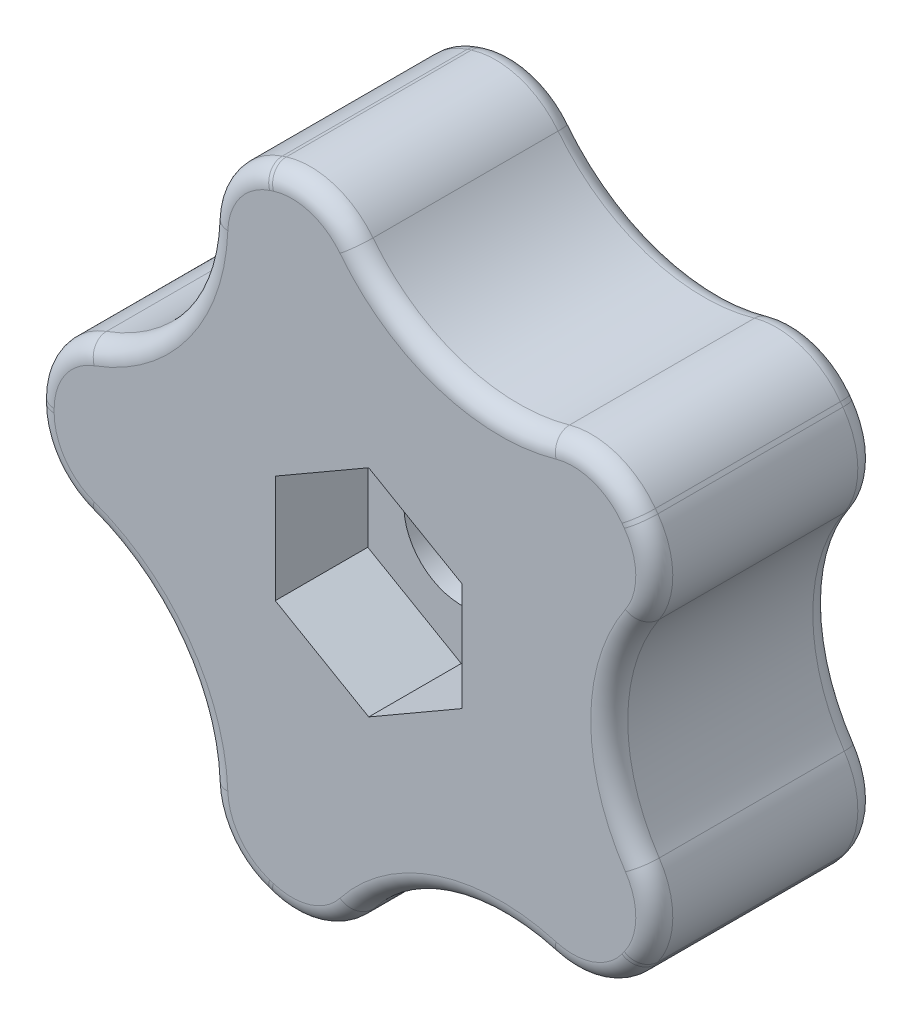
SolidWorks part; units mm, degrees
ref_plane "Plan de face" through (0, 0, 0) normal (0, 0, 1) x (1, 0, 0)
ref_plane "Plan de dessus" through (0, 0, 0) normal (0, 1, 0) x (1, 0, 0)
ref_plane "Plan de droite" through (0, 0, 0) normal (1, 0, 0) x (0, 0, -1)
sketch "Esquisse1" plane through (0, 0, 0) normal (0, 0, 1) x (1, 0, 0)
  circle A0 centre (0, 0) radius 18
  dimension "D1" = 36
extrude "Boss.-Extru.1" add sketch "Esquisse1" along normal blind 12
sketch "Esquisse2" plane through (0, 0, 0) normal (0, 0, -1) x (-1, 0, 0)
  circle A0 centre (0, 0) radius 6
  dimension "D1" = 12
extrude "Boss.-Extru.2" add sketch "Esquisse2" along normal blind 3
sketch "Esquisse3" plane through (0, 0, 12) normal (0, 0, 1) x (1, 0, 0)
  circle A0 centre (0, 0) radius 3.1
  dimension "D1" = 6.2
extrude "Enlèv. mat.-Extru.1" cut sketch "Esquisse3" against normal through all both and the other way through all
sketch "Esquisse4" plane through (0, 0, 12) normal (0, 0, 1) x (1, 0, 0)
  circle A0 centre (0, 0) radius 5
  dimension "D1" = 10
extrude "Enlèv. mat.-Extru.2" [suppressed] cut sketch "Esquisse4" against normal blind 8
sketch "Esquisse5" plane through (0, 0, 12) normal (0, 0, 1) x (1, 0, 0)
  line L0 (0, 0) -> (23, 0) construction
  arc A0 (16.3696, -7.4858) -> (16.3696, 7.4858) centre (23, 0) cw
  circle A1 centre (0, 0) radius 18 construction
  arc A2 (16.3696, -7.4858) -> (16.3696, 7.4858) centre (0, 0) ccw
  arc A3 (-2.061, -17.8816) -> (12.1779, -13.2551) centre (7.1074, -21.8743) cw
  arc A4 (-2.061, -17.8816) -> (12.1779, -13.2551) centre (0, 0) ccw
  arc A5 (-17.6433, -3.5656) -> (-8.8432, -15.6779) centre (-18.6074, -13.5191) cw
  arc A6 (-17.6433, -3.5656) -> (-8.8432, -15.6779) centre (0, 0) ccw
  arc A7 (-8.8432, 15.6779) -> (-17.6433, 3.5656) centre (-18.6074, 13.5191) cw
  arc A8 (-8.8432, 15.6779) -> (-17.6433, 3.5656) centre (0, 0) ccw
  arc A9 (12.1779, 13.2551) -> (-2.061, 17.8816) centre (7.1074, 21.8743) cw
  arc A10 (12.1779, 13.2551) -> (-2.061, 17.8816) centre (0, 0) ccw
  point P23 (0, 0)
  dimension "D1" = 10
  dimension "D2" = 23
  dimension "D3" = 5
extrude "Enlèv. mat.-Extru.3" cut sketch "Esquisse5" against normal through all both and the other way through all
fillet "Congé1" radius 4.3 10 edges at (-17.6433, -3.5656, 6) (-8.8432, -15.6779, 6) (-2.061, -17.8816, 6) (12.1779, -13.2551, 6) (16.3696, -7.4858, 6) (16.3696, 7.4858, 6) (12.1779, 13.2551, 6) (-2.061, 17.8816, 6) (-8.8432, 15.6779, 6) (-17.6433, 3.5656, 6)
fillet "Congé2" radius 1 40 edges at (-2.8824, -17.1651, 0) (4.0172, -12.3637, 0) (12.4213, -12.1927, 0) (14.5623, -10.5801, 0) (15.4343, -8.0456, 0) (13, 0, 0) (15.4343, 8.0456, 0) (14.5623, 10.5801, 0) (12.4213, 12.1927, 0) (4.0172, 12.3637, 0) (-2.8824, 17.1651, 0) (-5.5623, 17.119, 0) (-7.7575, 15.5811, 0) (-10.5172, 7.6412, 0) (-17.2157, 2.563, 0) (-18, 0, 0) (-17.2157, -2.563, 0) (-10.5172, -7.6412, 0) (-7.7575, -15.5811, 0) (-5.5623, -17.119, 0) (-17.2157, -2.563, 12) (-18, 0, 12) (-17.2157, 2.563, 12) (-10.5172, 7.6412, 12) (-7.7575, 15.5811, 12) (-5.5623, 17.119, 12) (-2.8824, 17.1651, 12) (4.0172, 12.3637, 12) (12.4213, 12.1927, 12) (14.5623, 10.5801, 12) (15.4343, 8.0456, 12) (13, 0, 12) (15.4343, -8.0456, 12) (14.5623, -10.5801, 12) (12.4213, -12.1927, 12) (4.0172, -12.3637, 12) (-2.8824, -17.1651, 12) (-5.5623, -17.119, 12) (-7.7575, -15.5811, 12) (-10.5172, -7.6412, 12)
chamfer "Chanfrein1" distance 1.5 angle 45 1 edges at (-6, 0, 0)
sketch "Esquisse6" plane through (0, 0, 12) normal (0, 0, 1) x (1, 0, 0)
  line L1 (5.05, -2.9156) -> (5.05, 2.9156)
  line L2 (5.05, 2.9156) -> (0, 5.8312)
  line L3 (0, 5.8312) -> (-5.05, 2.9156)
  line L4 (-5.05, 2.9156) -> (-5.05, -2.9156)
  line L5 (-5.05, -2.9156) -> (0, -5.8312)
  line L6 (0, -5.8312) -> (5.05, -2.9156)
  circle A0 centre (0, 0) radius 5.05 construction
  dimension "D1" = 10.1
extrude "Enlèv. mat.-Extru.4" cut sketch "Esquisse6" against normal blind 5
